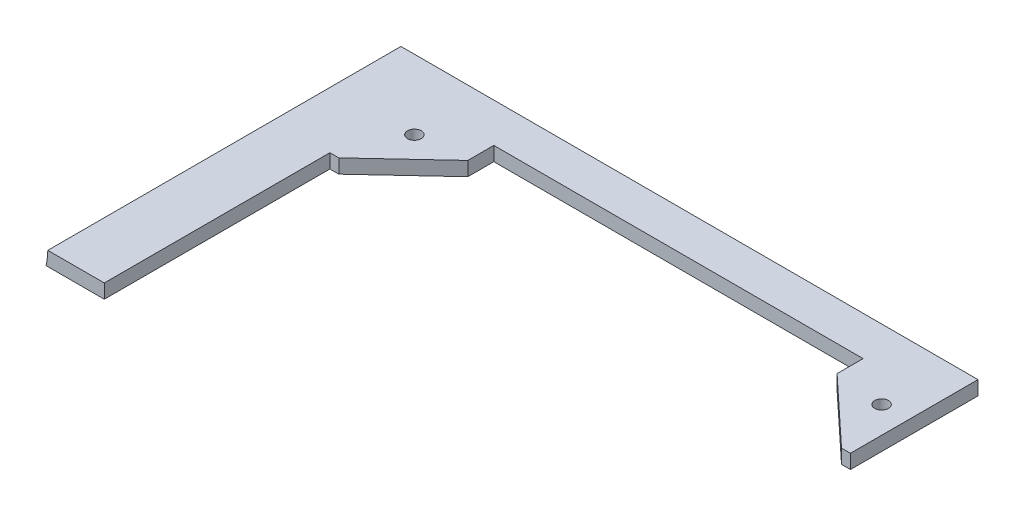
SolidWorks part; units mm, degrees
material "AISI 4130 Steel, annealed at 865C"
ref_plane "X-Y Datum" through (0, 0, 0) normal (0, 0, 1) x (1, 0, 0)
ref_plane "X-Z Datum" through (0, 0, 0) normal (0, 1, 0) x (1, 0, 0)
ref_plane "Y-Z Datum" through (0, 0, 0) normal (1, 0, 0) x (0, 0, -1)
sketch "Sketch1" plane through (0, 0, 0) normal (0, 1, 0) x (1, 0, 0)
  line L1 (-76.2, -38.1) -> (76.2, -38.1)
  line L2 (-76.2, -38.1) -> (-76.2, 38.1)
  line L3 (-76.2, 38.1) -> (76.2, 38.1)
  line L4 (76.2, -38.1) -> (76.2, 38.1)
  line L5 (-76.2, -38.1) -> (76.2, 38.1) construction
  line L6 (-76.2, 38.1) -> (76.2, -38.1) construction
  point P0 (0, 0)
  dimension "D1" = 152.4
  dimension "D2" = 76.2
extrude "Boss-Extrude1" add sketch "Sketch1" along normal blind 3.175 contours L3 L4 L1 L2
sketch "Sketch2" plane through (0, 3.175, 0) normal (0, 1, 0) x (1, 0, 0)
  line L0 (-56.5, 12.6) -> (-41.5, 26.6) construction
  line L1 (-41.5, 26.6) -> (-41.5, 32.45) construction
  line L2 (-41.5, 32.45) -> (41.5, 32.45) construction
  line L3 (41.5, 32.45) -> (41.5, 26.6) construction
  line L4 (-76.2, 38.1) -> (-76.2, -38.1)
  line L5 (-76.2, -38.1) -> (76.2, -38.1)
  line L6 (76.2, -38.1) -> (76.2, 38.1)
  line L7 (76.2, 38.1) -> (-76.2, 38.1)
  line L8 (-76.2, 38.1) -> (-76.2, -38.1)
  line L9 (-76.2, -38.1) -> (76.2, -38.1)
  line L10 (76.2, -38.1) -> (76.2, 38.1)
  line L11 (76.2, 38.1) -> (-76.2, 38.1)
  line L12 (41.5, 26.6) -> (56.5, 12.6) construction
  line L13 (-56.5, 12.6) -> (-41.5, 26.6)
  line L14 (-41.5, 26.6) -> (-41.5, 32.45)
  line L15 (-41.5, 32.45) -> (41.5, 32.45)
  line L16 (41.5, 32.45) -> (41.5, 26.6)
  line L17 (41.5, 26.6) -> (56.5, 12.6)
  line L18 (56.5, 12.6) -> (76.2, 12.6)
  line L19 (-56.5, 12.6) -> (-58.5, 12.6)
  line L20 (58.5, -451.9) -> (58.5, 38.1) construction
  line L21 (58.5, 12.6) -> (58.5, 38.1)
  line L22 (-58.5, 38.1) -> (-58.5, -451.9) construction
  line L23 (-58.5, 38.1) -> (-58.5, -38.1)
  circle A0 centre (-52.5052, 25.6052) radius 1.5453 construction
  circle A1 centre (52.5, 25.6052) radius 1.5453 construction
  circle A2 centre (-52.5052, 25.6052) radius 1.5453
  circle A3 centre (52.5, 25.6052) radius 1.5453
  line M6 (-76.2, -38.1) -> (76.2, -38.1)
  line M7 (76.2, -38.1) -> (76.2, 38.1)
  line M8 (76.2, 38.1) -> (-76.2, 38.1)
  dimension "D1" = 0
extrude "Cut-Extrude4" cut sketch "Sketch2" against normal through all contours L13 L19 L8 L18 L17 L16 L15 L14 M6 M7 | L21 L18 L10 M8 | A2 | A3
sketch "Sketch3" plane through (0, 0, -38.1) normal (0, 0, -1) x (-1, 0, 0)
  line L4 (76.2, 3.175) -> (-58.5, 3.175)
  line L5 (-58.5, 3.175) -> (-58.5, 0)
  line L6 (-58.5, 0) -> (76.2, 0)
  line L7 (76.2, 0) -> (76.2, 3.175)
  line L8 (76.2, 3.175) -> (-58.5, 3.175)
  line L9 (-58.5, 3.175) -> (-58.5, 0)
  line L10 (-58.5, 0) -> (76.2, 0)
  line L11 (76.2, 0) -> (76.2, 3.175)
  dimension "D1" = 0
extrude "Boss-Extrude2" add sketch "Sketch3" along normal blind 3.175
sketch "Sketch6" plane through (0, 0, 0) normal (0, -1, 0) x (1, 0, 0)
  line L0 (58.5, -41.275) -> (-76.2, -41.275) construction
  line L1 (58.5, -41.275) -> (-76.2, -41.275) construction
  line L14 (58.5, -38.1) -> (-76.2, -38.1) construction
  dimension "D1" = 3.175
sketch "Sketch7" plane through (0, 3.175, 0) normal (0, 1, 0) x (1, 0, 0)
  line L2 (-76.2, 38.1) -> (58.5, 38.1)
  line L3 (-76.2, 38.1) -> (58.5, 38.1) construction
  dimension "D1" = 3.175
sketch3d "3DSketch1"
  line L0 (-83.9, 3.175, 467.8839) -> (-83.9, 3.175, -36.6546)
  line L1 (-83.9, 3.175, -36.6546) -> (-83.9, 3.175, -210.1833)
  point P4 (-83.9, 3.175, -210.1833)
sweep "Cut-Sweep1" cut path "3DSketch1" circular profile diameter 25.4 parameters "D3"=25.4
